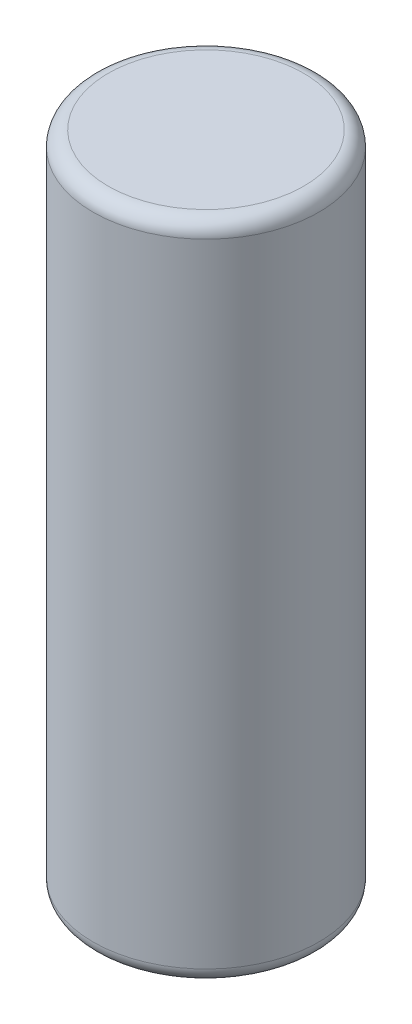
SolidWorks part; units mm, degrees
ref_plane "Front Plane" through (0, 0, 0) normal (0, 0, 1) x (1, 0, 0)
ref_plane "Top Plane" through (0, 0, 0) normal (0, 1, 0) x (1, 0, 0)
ref_plane "Right Plane" through (0, 0, 0) normal (1, 0, 0) x (0, 0, -1)
sketch "Sketch2" plane through (0, 0, 0) normal (0, 1, 0) x (1, 0, 0)
  circle A0 centre (0, 0) radius 75
  dimension "D1" = 150
extrude "Boss-Extrude1" add sketch "Sketch2" along normal blind 440
fillet "Fillet1" radius 10 2 edges at (0, 0, 75) (0, 440, 75)
